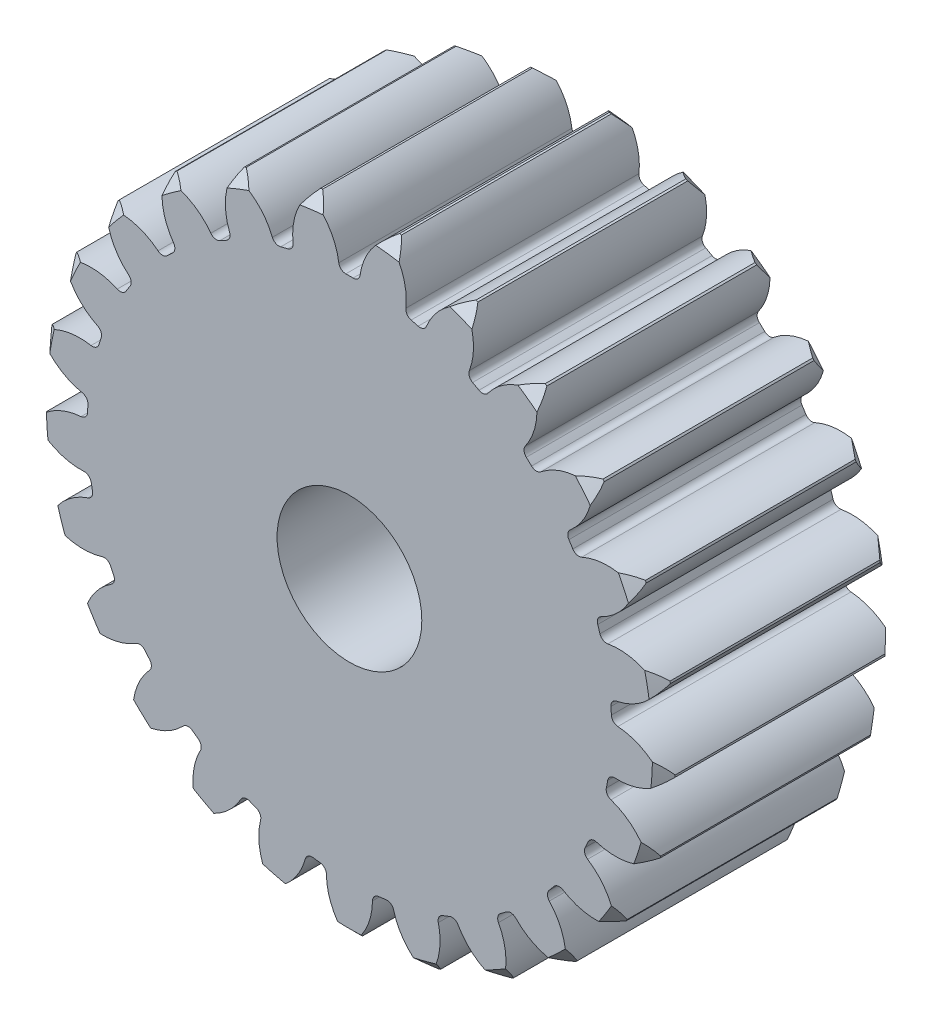
SolidWorks part; units mm, degrees
material "AISI 316 Stainless Steel Sheet (SS)"
ref_plane "Front Plane" through (0, 0, 0) normal (0, 0, 1) x (1, 0, 0)
ref_plane "Top Plane" through (0, 0, 0) normal (0, 1, 0) x (1, 0, 0)
ref_plane "Right Plane" through (0, 0, 0) normal (1, 0, 0) x (0, 0, -1)
sketch "Sketch2" plane through (0, 0, 0) normal (0, 0, 1) x (1, 0, 0)
  circle A1 centre (0, 0) radius 25 construction
  circle A2 centre (0, 0) radius 27
  dimension "D1" = 50
  dimension "D2" = 54
extrude "Boss-Extrude2" add sketch "Sketch2" along normal mid plane 20 contours A2
chamfer "Chamfer1" distance 1 angle 45 2 edges at (27, 0, -10) (27, 0, 10)
sketch "Sketch3" plane through (0, 0, 0) normal (0, 0, 1) x (1, 0, 0)
  line L0 (0, 22.184) -> (0, 22.5) construction
  line L1 (0, 0) -> (2.82, 22.3226) construction
  line L2 (0, 0) -> (6.7146, 26.1517) construction
  line L4 (-1.5698, 24.9507) -> (0, 24.9507) construction
  line L5 (-0.4604, 22.9954) -> (0, 22.184) construction
  circle A3 centre (0, 0) radius 27 construction
  arc A4 (-3.2954, 26.7981) -> (-0.8674, 22.4833) centre (-6.287, 22.2742) cw
  circle A5 centre (0, 0) radius 27 construction
  arc A6 (3.2954, 26.7981) -> (0.8674, 22.4833) centre (6.287, 22.2742) ccw
  arc A7 (0.8674, 22.4833) -> (-0.8674, 22.4833) centre (0, 0) ccw
  arc A10 (3.2954, 26.7981) -> (-3.2954, 26.7981) centre (0, 0) ccw
  point P15 (0, 0)
  dimension "D3" = 14.4
extrude "Cut-Extrude1" cut sketch "Sketch3" against normal mid plane 20 contours A6 A7 A4 A10
fillet "Fillet1" radius 0.6 2 edges at (0.8674, 22.4833, 0) (-0.8674, 22.4833, 0)
pattern_circular "CirPattern1" count 25 over 360 about axis through (0, 0, 0) along (0, 0, 1) of "Cut-Extrude1", "Fillet1"
sketch "Sketch5" plane through (0, 0, 0) normal (0, 0, 1) x (1, 0, 0)
  arc A0 (3.2954, 26.7981) -> (2.2553, 25.902) centre (6.287, 22.2742) ccw construction
  arc A1 (2.2553, 25.902) -> (0.9143, 23.0157) centre (6.287, 22.2742) ccw construction
  arc A2 (-0.9143, 23.0157) -> (-2.2553, 25.902) centre (-6.287, 22.2742) ccw construction
  arc A3 (0.3116, 22.4978) -> (-0.3116, 22.4978) centre (0, 0) ccw construction
  arc A4 (0.3116, 22.4978) -> (0.9143, 23.0157) centre (0.3199, 23.0978) ccw construction
  arc A5 (-0.9143, 23.0157) -> (-0.3116, 22.4978) centre (-0.3199, 23.0978) ccw construction
  arc A6 (-2.2553, 25.902) -> (-3.2954, 26.7981) centre (-6.287, 22.2742) ccw construction
  arc A7 (3.2954, 26.7981) -> (2.2553, 25.902) centre (6.287, 22.2742) ccw
  arc A8 (2.2553, 25.902) -> (0.9143, 23.0157) centre (6.287, 22.2742) ccw
  arc A9 (-0.9143, 23.0157) -> (-2.2553, 25.902) centre (-6.287, 22.2742) ccw
  arc A10 (0.3116, 22.4978) -> (-0.3116, 22.4978) centre (0, 0) ccw
  arc A11 (0.3116, 22.4978) -> (0.9143, 23.0157) centre (0.3199, 23.0978) ccw
  arc A12 (-0.9143, 23.0157) -> (-0.3116, 22.4978) centre (-0.3199, 23.0978) ccw
  arc A13 (-2.2553, 25.902) -> (-3.2954, 26.7981) centre (-6.287, 22.2742) ccw
  arc A14 (-9.8563, 25.1367) -> (-10.0223, 25.071) centre (0, 0) ccw construction
  arc A15 (-8.626, 24.5274) -> (-9.8563, 25.1367) centre (-11.6288, 20.0109) ccw construction
  arc A16 (-6.6094, 22.0653) -> (-8.626, 24.5274) centre (-11.6288, 20.0109) ccw construction
  arc A17 (-6.6094, 22.0653) -> (-5.8968, 21.7135) centre (-6.0541, 22.2926) ccw construction
  arc A18 (-5.2932, 21.8685) -> (-5.8968, 21.7135) centre (0, 0) ccw construction
  arc A19 (-5.2932, 21.8685) -> (-4.8382, 22.52) centre (-5.4343, 22.4517) ccw construction
  arc A20 (-4.2571, 25.6491) -> (-4.8382, 22.52) centre (0.5501, 23.1379) ccw construction
  arc A21 (-3.4725, 26.7758) -> (-4.2571, 25.6491) centre (0.5501, 23.1379) ccw construction
  arc A22 (-9.8563, 25.1367) -> (-10.0223, 25.071) centre (0, 0) ccw
  arc A23 (-8.626, 24.5274) -> (-9.8563, 25.1367) centre (-11.6288, 20.0109) ccw
  arc A24 (-6.6094, 22.0653) -> (-8.626, 24.5274) centre (-11.6288, 20.0109) ccw
  arc A25 (-6.6094, 22.0653) -> (-5.8968, 21.7135) centre (-6.0541, 22.2926) ccw
  arc A26 (-5.2932, 21.8685) -> (-5.8968, 21.7135) centre (0, 0) ccw
  arc A27 (-5.2932, 21.8685) -> (-4.8382, 22.52) centre (-5.4343, 22.4517) ccw
  arc A28 (-4.2571, 25.6491) -> (-4.8382, 22.52) centre (0.5501, 23.1379) ccw
  arc A29 (-3.4725, 26.7758) -> (-4.2571, 25.6491) centre (0.5501, 23.1379) ccw
  circle A30 centre (0, 0) radius 6.2088
extrude "Cut-Extrude2" cut sketch "Sketch5" against normal through all both and the other way through all contours A30
equation "\"Module\"= 2mm"
equation "\"Number of teeth\"= 25"
equation "\"Pressure\"=29.57"
equation "\"D1@Sketch2\"=\"Module\"*\"Number of teeth\""
equation "\"D2@Sketch2\"=(\"Number of teeth\"+ 2)* \"Module\""
equation "\"D1@Chamfer1\"=\"Module\"/2"
equation "\"D3@Sketch3\"=360 / \"Number of teeth\""
equation "\"D1@Fillet1\"=0.3 * \"Module\""
equation "\"D1@CirPattern1\"= \"Number of teeth\""
